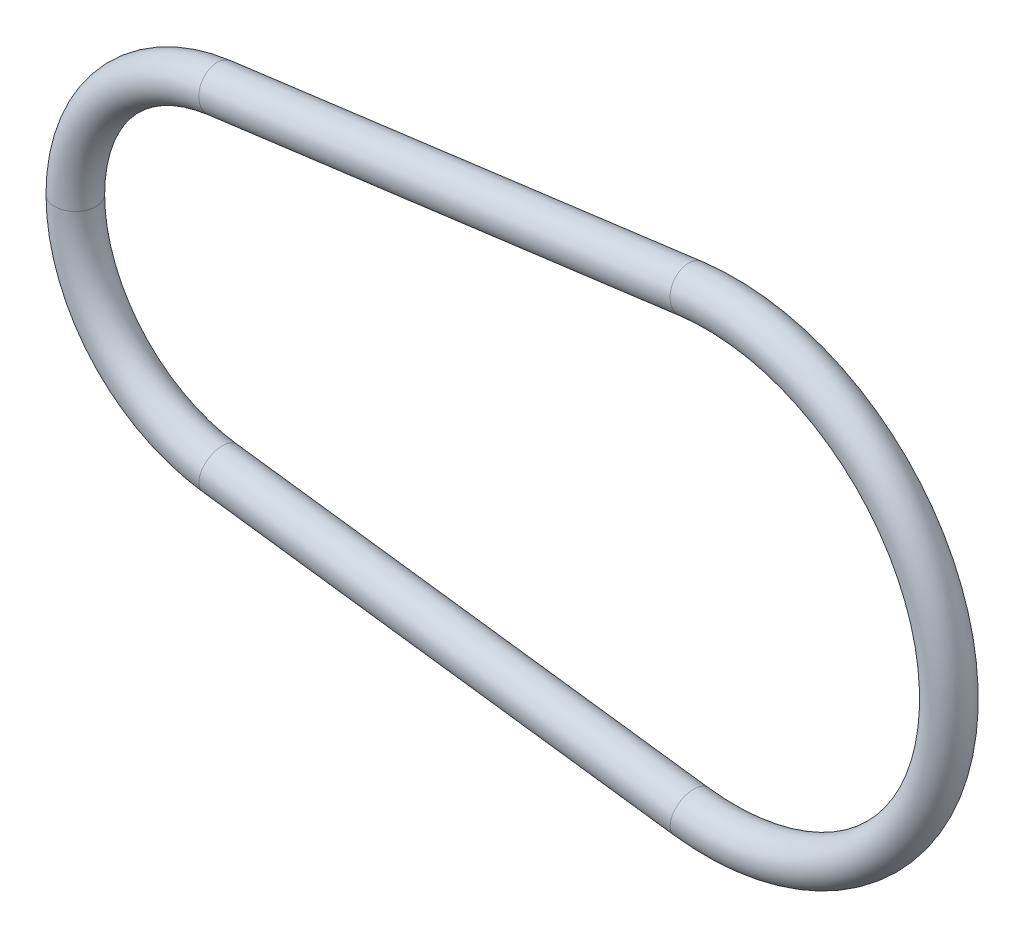
SolidWorks part; units mm, degrees
ref_plane "Front Plane" through (0, 0, 0) normal (0, 0, 1) x (1, 0, 0)
ref_plane "Top Plane" through (0, 0, 0) normal (0, 1, 0) x (1, 0, 0)
ref_plane "Right Plane" through (0, 0, 0) normal (1, 0, 0) x (0, 0, -1)
sketch "Sketch2" plane through (0, 0, 0) normal (0, 0, 1) x (1, 0, 0)
  line L0 (-2.0777, 15.8645) -> (43.3482, 21.8137)
  line L1 (-2.0777, -15.8645) -> (43.3482, -21.8137)
  arc A1 (-2.0777, -15.8645) -> (-2.0777, 15.8645) centre (0, 0) cw
  arc A2 (43.3482, 21.8137) -> (43.3482, -21.8137) centre (46.205, 0) cw
  dimension "D1" = 16
  dimension "D2" = 22
sketch "Sketch3" plane through (0, 0, 0) normal (0, 1, 0) x (1, 0, 0)
  line L1 (0, 5.5) -> (0, -5.5) construction
  circle A0 centre (-16, 0) radius 2
  dimension "D1" = 4
  dimension "D2" = 16
sweep "Sweep1" add profiles "Sketch3" path "Sketch2"
